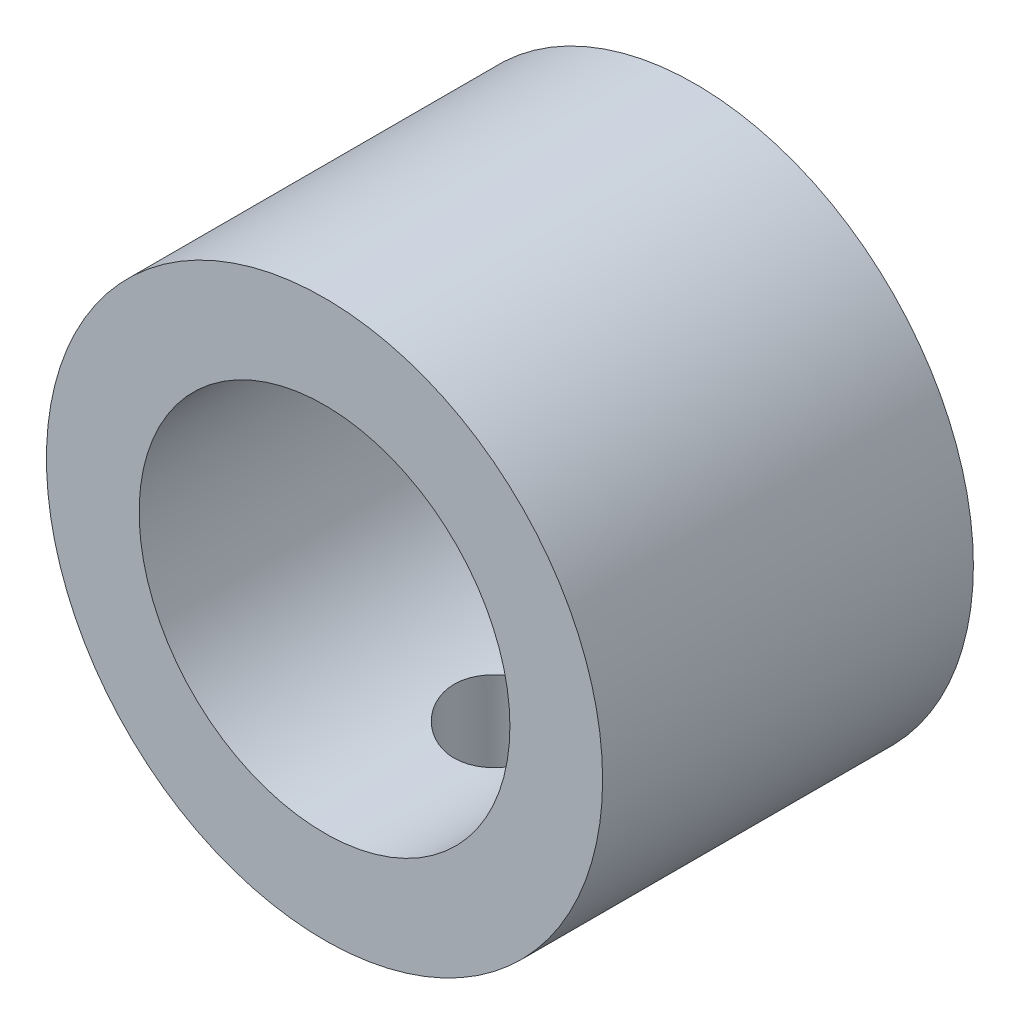
SolidWorks part; units mm, degrees
ref_plane "Front Plane" through (0, 0, 0) normal (0, 0, 1) x (1, 0, 0)
ref_plane "Top Plane" through (0, 0, 0) normal (0, 1, 0) x (1, 0, 0)
ref_plane "Right Plane" through (0, 0, 0) normal (1, 0, 0) x (0, 0, -1)
sketch "Sketch1" plane through (0, 0, 0) normal (0, 0, 1) x (1, 0, 0)
  circle A0 centre (0, 0) radius 5
  circle A1 centre (0, 0) radius 7.5
  dimension "D1" = 10
  dimension "D2" = 15
extrude "Boss-Extrude3" add sketch "Sketch1" along normal mid plane 10 contours A0 | A1
sketch "Sketch10" plane through (0, 0, 0) normal (0, 1, 0) x (1, 0, 0)
  circle A0 centre (0, 0) radius 1.5
  dimension "D1" = 3
extrude "Cut-Extrude4" cut sketch "Sketch10" against normal up to surface (7.5 mm away) contours A0
